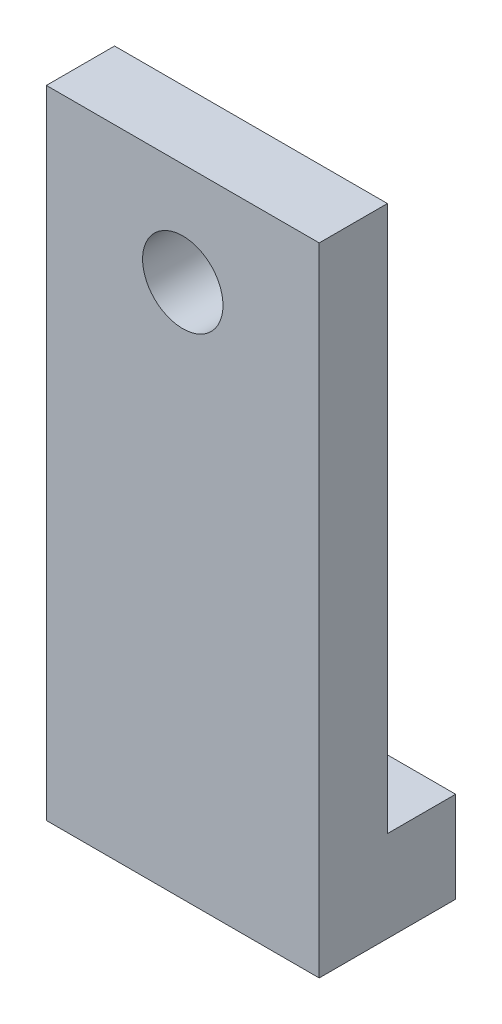
SolidWorks part; units mm, degrees
ref_plane "Front" through (0, 0, 0) normal (0, 0, 1) x (1, 0, 0)
ref_plane "Top" through (0, 0, 0) normal (0, 1, 0) x (1, 0, 0)
ref_plane "Right" through (0, 0, 0) normal (1, 0, 0) x (0, 0, -1)
sketch "Sketch1" plane through (0, 0, 0) normal (1, 0, 0) x (0, 0, -1)
  line L0 (0, 0) -> (-9.525, 0)
  line L1 (-9.525, 0) -> (-9.525, 44.45)
  line L2 (-9.525, 44.45) -> (-4.7625, 44.45)
  line L3 (-4.7625, 44.45) -> (-4.7625, 6.35)
  line L4 (-4.7625, 6.35) -> (0, 6.35)
  line L5 (0, 6.35) -> (0, 0)
  dimension "D1" = 44.45
  dimension "D2" = 6.35
  dimension "D3" = 9.525
  dimension "D4" = 4.7625
extrude "Extrude1" add sketch "Sketch1" along normal blind 19.05
hole_wizard "#10 Clearance Hole1" positions "Sketch3" profile "Sketch2" hole size "#10" standard "Ansi Inch" end condition through all
sketch "Sketch3" plane through (0, 0, 9.525) normal (0, 0, 1) x (1, 0, 0)
  line L0 (19.05, 44.45) -> (19.05, 0) construction
  line L1 (19.05, 0) -> (0, 0) construction
  point P0 (9.525, 37.3062)
  dimension "D1" = 9.525
  dimension "D2" = 37.3062
sketch "Sketch2" plane through (9.525, 37.3062, 9.525) normal (1, 0, 0) x (0, -1, 0)
  line L0 (0, 0) -> (0, 9.525)
  line L1 (0, 9.525) -> (2.8067, 9.525)
  line L2 (2.8067, 9.525) -> (2.8067, 0)
  line L5 (2.8067, 0) -> (0, 0)
  line L11 (0, -6.35) -> (0, 107.95) construction
  dimension "Thru Hole Dia." = 5.6134
  dimension "Thru Hole Depth" = 9.525
